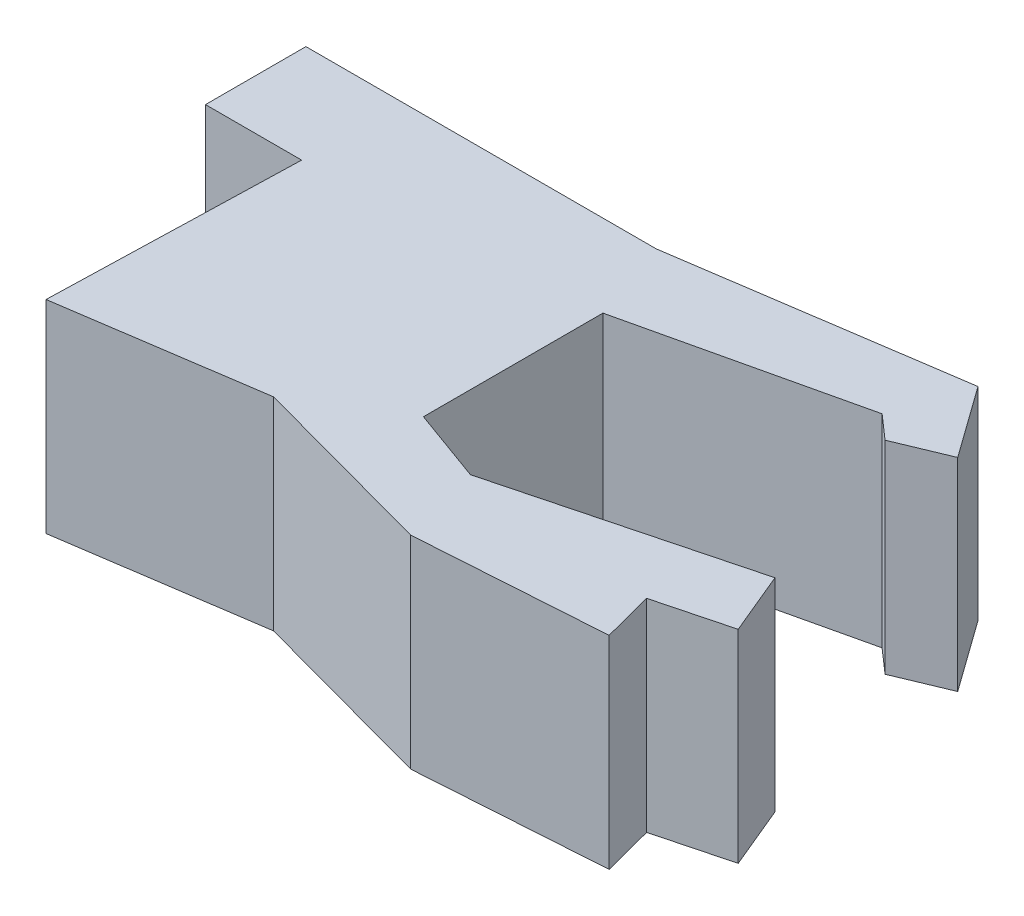
SolidWorks part; units mm, degrees
ref_plane "前视基准面" through (0, 0, 0) normal (0, 0, 1) x (1, 0, 0)
ref_plane "上视基准面" through (0, 0, 0) normal (0, 1, 0) x (1, 0, 0)
ref_plane "右视基准面" through (0, 0, 0) normal (1, 0, 0) x (0, 0, -1)
sketch "草图2" plane through (0, 0, 0) normal (0, 1, 0) x (1, 0, 0)
  line L0 (-120.893, 54.8556) -> (-69.0272, 54.8556)
  line L1 (-130.2226, 69.6927) -> (-10.2226, 69.6927) construction
  line L2 (-130.2226, 69.6927) -> (-130.2226, -10.3073) construction
  line L3 (-130.2226, -10.3073) -> (-10.2226, -10.3073) construction
  line L4 (-10.2226, 69.6927) -> (-10.2226, -10.3073) construction
  line L5 (-69.0272, 54.8556) -> (-27.5979, 61.0226)
  line L6 (-27.5979, 61.0226) -> (-20.0078, 50.428)
  line L7 (-20.0078, 50.428) -> (-27.5979, 47.2655)
  line L8 (-27.5979, 47.2655) -> (-31.1969, 50.428)
  line L9 (-31.1969, 50.428) -> (-64.7578, 42.6798)
  line L10 (-64.7578, 42.6798) -> (-64.7578, 16.1144)
  line L11 (-64.7578, 16.1144) -> (-53.847, 12.1612)
  line L12 (-53.847, 12.1612) -> (-18.1102, 21.4907)
  line L13 (-18.1102, 21.4907) -> (-14.2229, 12.1612)
  line L14 (-14.2229, 12.1612) -> (-24.9687, 9.3559)
  line L15 (-24.9687, 9.3559) -> (-23.0056, 1.8364)
  line L16 (-23.0056, 1.8364) -> (-50.5263, 0)
  line L17 (-50.5263, 0) -> (-78.4009, 7.5746)
  line L18 (-78.4009, 7.5746) -> (-107.7139, 3.2112)
  line L19 (-107.7139, 3.2112) -> (-106.6616, 39.9916)
  line L20 (-106.6616, 39.9916) -> (-120.893, 39.9916)
  line L21 (-120.893, 39.9916) -> (-120.893, 54.8556)
  point P23 (0, 0)
  dimension "D1" = 120
  dimension "D2" = 80
extrude "凸台-拉伸1" add sketch "草图2" along normal blind 30
